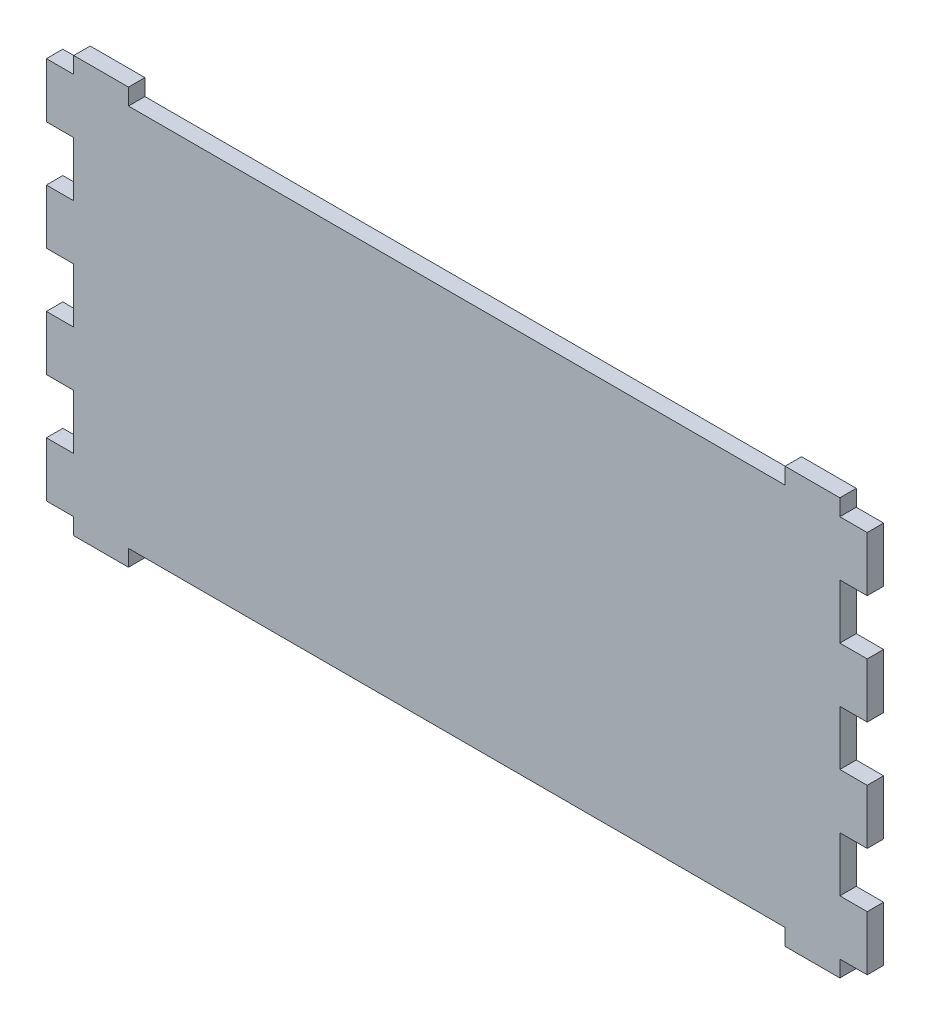
SolidWorks part; units mm, degrees
ref_plane "Plano frontal" through (0, 0, 0) normal (0, 0, 1) x (1, 0, 0)
ref_plane "Plano superior" through (0, 0, 0) normal (0, 1, 0) x (1, 0, 0)
ref_plane "Plano direito" through (0, 0, 0) normal (1, 0, 0) x (0, 0, -1)
sketch "Esboço1" plane through (0, 0, 0) normal (0, 0, 1) x (1, 0, 0)
  line L1 (70, -35) -> (-70, -35)
  line L2 (70, -35) -> (70, 35)
  line L3 (70, 35) -> (-70, 35)
  line L4 (-70, -35) -> (-70, 35)
  line L5 (70, -35) -> (-70, 35) construction
  line L6 (70, 35) -> (-70, -35) construction
  line L7 (-70, 35) -> (-60, 35)
  line L8 (-70, 35) -> (-70, 38)
  line L9 (-70, 38) -> (-60, 38)
  line L10 (-60, 35) -> (-60, 38)
  line L11 (70, 35) -> (60, 35)
  line L12 (70, 35) -> (70, 38)
  line L13 (70, 38) -> (60, 38)
  line L14 (60, 35) -> (60, 38)
  line L15 (70, -35) -> (60, -35)
  line L16 (70, -35) -> (70, -38)
  line L17 (70, -38) -> (60, -38)
  line L18 (60, -35) -> (60, -38)
  line L19 (-70, -35) -> (-60, -35)
  line L20 (-70, -35) -> (-70, -38)
  line L21 (-70, -38) -> (-60, -38)
  line L22 (-60, -35) -> (-60, -38)
  point P0 (0, 0)
  dimension "D1" = 70
  dimension "D2" = 140
  dimension "D3" = 10
  dimension "D4" = 3
  dimension "D5" = 3
  dimension "D6" = 10
  dimension "D7" = 10
  dimension "D8" = 3
  dimension "D9" = 10
  dimension "D10" = 3
extrude "Ressalto-extrusão1" add sketch "Esboço1" along normal blind 3 contours L3 L10 L9 L8 | L1 L18 L17 L16 | L22 L1 L20 L21 | L4 L1 L2 L3 | L12 L13 L14 L11
sketch "Esboço2" plane through (0, 0, 3) normal (0, 0, 1) x (1, 0, 0)
  line L0 (70, -38) -> (70, 38) construction
  line L1 (70, 35) -> (75, 35)
  line L2 (70, 35) -> (70, 25)
  line L3 (70, 25) -> (75, 25)
  line L4 (75, 35) -> (75, 25)
  line L5 (0, 35) -> (0, -35)
  line L14 (70, -5) -> (75, -5)
  line L15 (70, -5) -> (70, -15)
  line L16 (70, -15) -> (75, -15)
  line L17 (75, -5) -> (75, -15)
  line L18 (70, 15) -> (75, 15)
  line L19 (70, 15) -> (70, 5)
  line L20 (70, 5) -> (75, 5)
  line L21 (75, 15) -> (75, 5)
  line L22 (70, -25) -> (75, -25)
  line L23 (70, -25) -> (70, -35)
  line L24 (70, -35) -> (75, -35)
  line L25 (75, -25) -> (75, -35)
  line L26 (60, 35) -> (-60, 35) construction
  line L27 (60, -35) -> (-60, -35) construction
  line L28 (-70, -35) -> (-75, -35)
  line L29 (-75, -25) -> (-75, -35)
  line L30 (-70, -25) -> (-75, -25)
  line L31 (-70, -25) -> (-70, -35)
  line L32 (-70, -15) -> (-75, -15)
  line L33 (-75, -5) -> (-75, -15)
  line L34 (-70, -5) -> (-75, -5)
  line L35 (-70, -5) -> (-70, -15)
  line L36 (-70, 5) -> (-75, 5)
  line L37 (-75, 15) -> (-75, 5)
  line L38 (-70, 15) -> (-75, 15)
  line L39 (-70, 15) -> (-70, 5)
  line L40 (-70, 25) -> (-75, 25)
  line L41 (-75, 35) -> (-75, 25)
  line L42 (-70, 35) -> (-75, 35)
  line L43 (-70, 35) -> (-70, 25)
  line M17 (-70, 38) -> (-70, -38)
  line M23 (70, -38) -> (70, 38)
  dimension "D1" = 5
  dimension "D2" = 10
  dimension "D3" = 10
  dimension "D4" = 10
  dimension "D5" = 5
  dimension "D6" = 10
  dimension "D7" = 10
  dimension "D8" = 5
  dimension "D9" = 10
  dimension "D10" = 10
  dimension "D11" = 5
extrude "Ressalto-extrusão2" add sketch "Esboço2" against normal blind 3 contours L30 L29 L28 M17 | L34 L33 L32 M17 | L38 L37 L36 M17 | L42 L41 L40 M17 | L4 L1 L3 M23 | L21 L18 L20 M23 | L17 L14 L16 M23 | L25 L22 L24 M23
